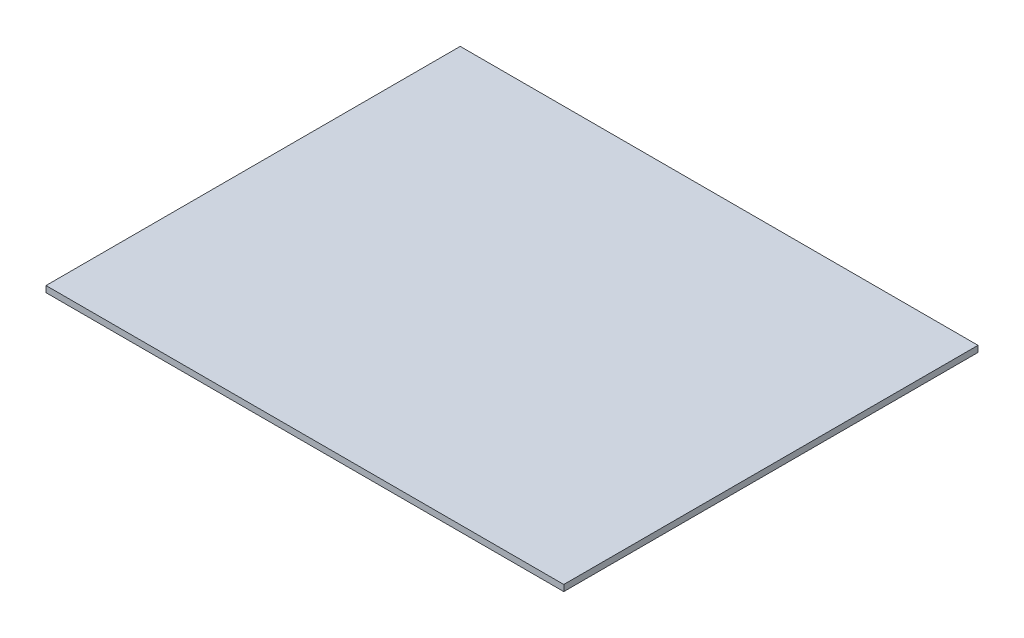
SolidWorks part; units mm, degrees
ref_plane "Front Plane" through (0, 0, 0) normal (0, 0, 1) x (1, 0, 0)
ref_plane "Top Plane" through (0, 0, 0) normal (0, 1, 0) x (1, 0, 0)
ref_plane "Right Plane" through (0, 0, 0) normal (1, 0, 0) x (0, 0, -1)
sketch "Sketch1" plane through (0, 0, 0) normal (0, 1, 0) x (1, 0, 0)
  line L1 (500, 400) -> (-500, 400)
  line L2 (500, 400) -> (500, -400)
  line L3 (500, -400) -> (-500, -400)
  line L4 (-500, 400) -> (-500, -400)
  line L5 (500, 400) -> (-500, -400) construction
  line L6 (500, -400) -> (-500, 400) construction
  point P0 (0, 0)
  dimension "800" = 800
  dimension "D2" = 1000
extrude "Boss-Extrude1" add sketch "Sketch1" along normal blind 12
